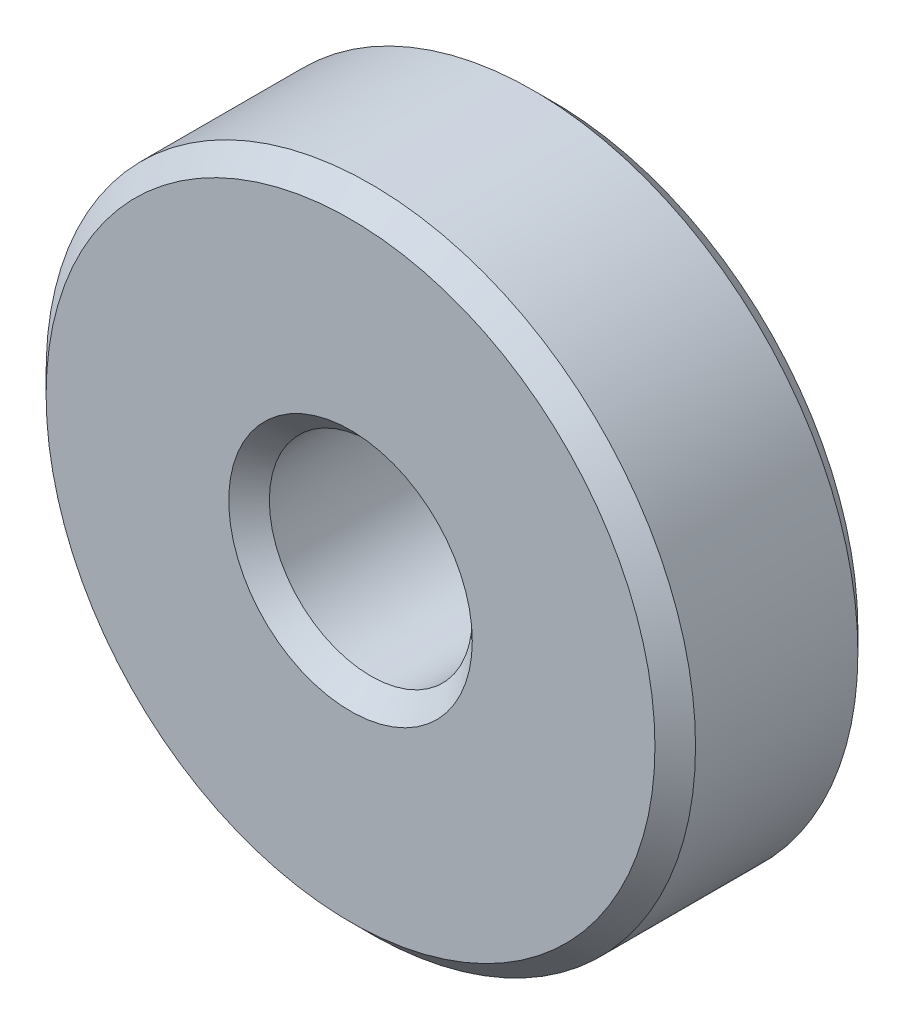
SolidWorks part; units mm, degrees
ref_plane "Front" through (0, 0, 0) normal (0, 0, 1) x (1, 0, 0)
ref_plane "Top" through (0, 0, 0) normal (0, 1, 0) x (1, 0, 0)
ref_plane "Right" through (0, 0, 0) normal (1, 0, 0) x (0, 0, -1)
sketch "Esquisse1" plane through (0, 0, 0) normal (0, 0, 1) x (1, 0, 0)
  circle A0 centre (0, 0) radius 2.5
  circle A1 centre (0, 0) radius 8
  dimension "D1" = 5
  dimension "D2" = 16
extrude "Boss.-Extru.1" add sketch "Esquisse1" along normal blind 5
chamfer "Chanfrein1" distance 0.5 angle 45 4 edges at (2.5, 0, 0) (8, 0, 0) (2.5, 0, 5) (8, 0, 5)
